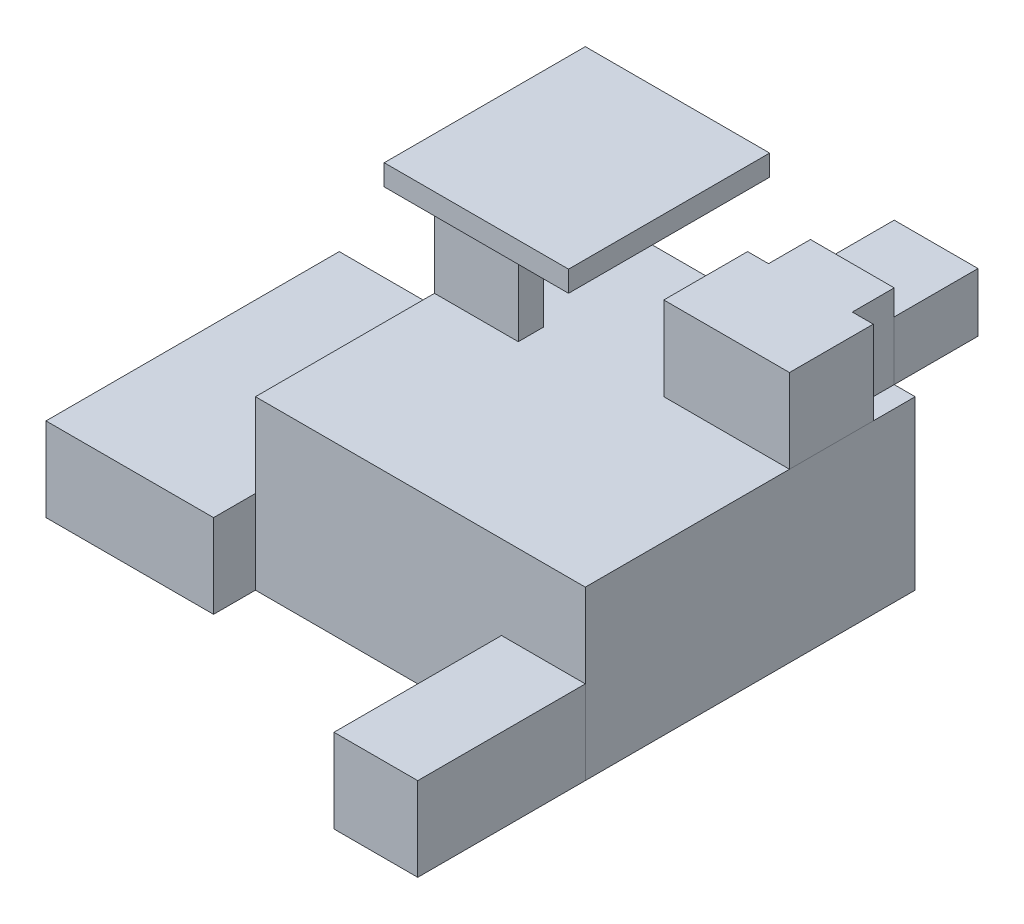
SolidWorks part; units mm, degrees
ref_plane "Front Plane" through (0, 0, 0) normal (0, 0, 1) x (1, 0, 0)
ref_plane "Top Plane" through (0, 0, 0) normal (0, 1, 0) x (1, 0, 0)
ref_plane "Right Plane" through (0, 0, 0) normal (1, 0, 0) x (0, 0, -1)
sketch "Sketch1" plane through (0, 0, 0) normal (0, 1, 0) x (1, 0, 0)
  line L1 (0, 0) -> (50, 0)
  line L2 (0, 0) -> (0, 50)
  line L3 (0, 50) -> (50, 50)
  line L4 (50, 0) -> (50, 50)
extrude "main boards" add sketch "Sketch1" along normal blind 25.4
sketch "Sketch2" plane through (0, 0, 0) normal (0, 0, 1) x (1, 0, 0)
  line L1 (50, 0) -> (37.3, 0)
  line L2 (50, 0) -> (50, 12.7)
  line L3 (50, 12.7) -> (37.3, 12.7)
  line L4 (37.3, 0) -> (37.3, 12.7)
extrude "USB" add sketch "Sketch2" along normal blind 25.4 separate body
sketch "Sketch3" plane through (0, 0, 0) normal (-1, 0, 0) x (0, 0, 1)
  line L0 (0, 25.4) -> (0, 0) construction
  line L1 (6.35, 0) -> (-38.1, 0)
  line L2 (6.35, 0) -> (6.35, 12.7)
  line L3 (6.35, 12.7) -> (-38.1, 12.7)
  line L4 (-38.1, 0) -> (-38.1, 12.7)
  dimension "D1" = 6.35
  dimension "D2" = 38.1
  dimension "D3" = 12.7
extrude "PICKIT" add sketch "Sketch3" along normal blind 25.4 separate body
sketch "Sketch4" plane through (0, 25.4, 0) normal (0, 1, 0) x (1, 0, 0)
  line L0 (50, 0) -> (50, 50) construction
  line L1 (50, 43.65) -> (46.825, 43.65)
  line L2 (50, 43.65) -> (50, 30.95)
  line L3 (50, 30.95) -> (30.95, 30.95)
  line L4 (30.95, 43.65) -> (30.95, 30.95)
  line L5 (50, 50) -> (0, 50) construction
  line L6 (34.125, 43.65) -> (30.95, 43.65)
  line L8 (46.825, 43.65) -> (46.825, 50)
  line L9 (46.825, 50) -> (34.125, 50)
  line L10 (34.125, 43.65) -> (34.125, 50)
  dimension "D1" = 6.35
  dimension "D2" = 12.7
  dimension "D3" = 19.05
  dimension "D4" = 3.175
  dimension "D5" = 12.7
extrude "hbridge" add sketch "Sketch4" along normal blind 12.7 separate body
sketch "Sketch5" plane through (0, 25.4, 0) normal (0, 1, 0) x (1, 0, 0)
  line L1 (46.825, 50) -> (34.125, 50)
  line L2 (46.825, 50) -> (46.825, 62.7)
  line L3 (46.825, 62.7) -> (34.125, 62.7)
  line L4 (34.125, 50) -> (34.125, 62.7)
  line L5 (50, 0) -> (50, 50) construction
  line L6 (46.825, 50) -> (34.125, 50) construction
  dimension "D1" = 3.175
  dimension "D2" = 12.7
  dimension "D3" = 12.7
extrude "motor wiring" add sketch "Sketch5" along normal blind 8.89 separate body
sketch "Sketch6" plane through (0, 25.4, 0) normal (0, 1, 0) x (1, 0, 0)
  line L0 (0, 50) -> (0, 0) construction
  line L1 (12.7, 30.95) -> (0, 30.95)
  line L2 (12.7, 30.95) -> (12.7, 27.14)
  line L3 (12.7, 27.14) -> (0, 27.14)
  line L4 (0, 30.95) -> (0, 27.14)
  line L5 (30.95, 30.95) -> (50, 30.95) construction
  dimension "D1" = 12.7
  dimension "D2" = 3.81
extrude "header" add sketch "Sketch6" along normal blind 11.43 separate body
sketch "Sketch7" plane through (0, 36.83, 0) normal (0, 1, 0) x (1, 0, 0)
  line L0 (0, 50) -> (0, 0) construction
  line L1 (21.59, 25.87) -> (-6.35, 25.87)
  line L2 (21.59, 25.87) -> (21.59, 56.35)
  line L3 (21.59, 56.35) -> (-6.35, 56.35)
  line L4 (-6.35, 25.87) -> (-6.35, 56.35)
  line L5 (0, 27.14) -> (12.7, 27.14) construction
  line L6 (50, 50) -> (0, 50) construction
  dimension "D1" = 6.35
  dimension "D2" = 27.94
  dimension "D3" = 1.27
  dimension "D4" = 6.35
extrude "OLED" add sketch "Sketch7" along normal blind 3.175 separate body
